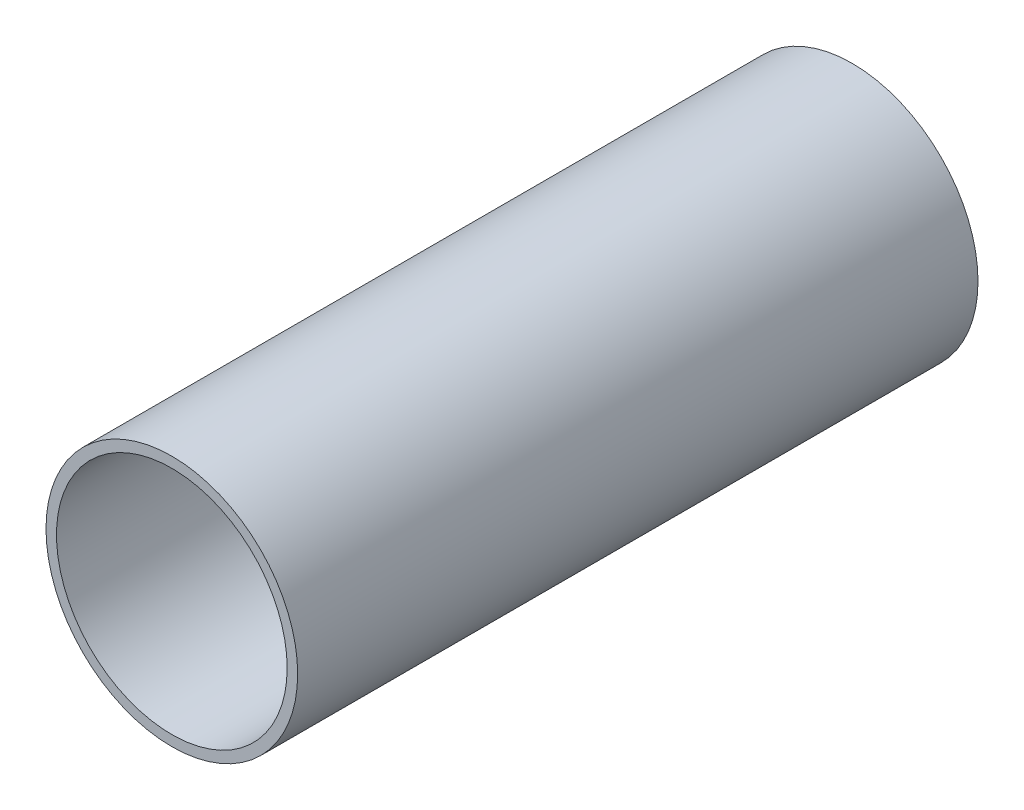
SolidWorks part; units mm, degrees
ref_plane "Front Plane" through (0, 0, 0) normal (0, 0, 1) x (1, 0, 0)
ref_plane "Top Plane" through (0, 0, 0) normal (0, 1, 0) x (1, 0, 0)
ref_plane "Right Plane" through (0, 0, 0) normal (1, 0, 0) x (0, 0, -1)
sketch "Sketch1" plane through (0, 0, 0) normal (0, 0, 1) x (1, 0, 0)
  circle A0 centre (0, 0) radius 69.85
  circle A1 centre (0, 0) radius 76.2
  dimension "D1" = 139.7
  dimension "D2" = 152.4
extrude "Boss-Extrude1" add sketch "Sketch1" along normal blind 412
